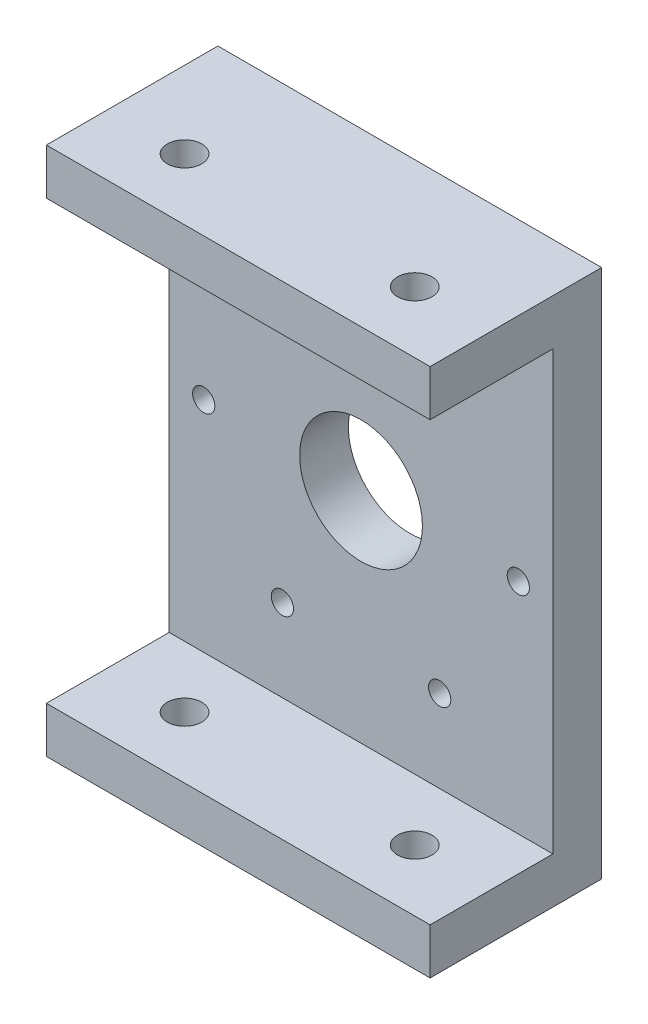
SolidWorks part; units mm, degrees
material "Aleación 6061"
ref_plane "Alzado" through (0, 0, 0) normal (0, 0, 1) x (1, 0, 0)
ref_plane "Planta" through (0, 0, 0) normal (0, 1, 0) x (1, 0, 0)
ref_plane "Vista lateral" through (0, 0, 0) normal (1, 0, 0) x (0, 0, -1)
sketch "Sk_Repisa" plane through (0, 0, 0) normal (0, 0, 1) x (1, 0, 0)
  line L1 (-25, -34.5) -> (25, -34.5)
  line L2 (-25, -34.5) -> (-25, 34.5)
  line L3 (-25, 34.5) -> (25, 34.5)
  line L4 (25, -34.5) -> (25, 34.5)
  line L5 (-25, -34.5) -> (25, 34.5) construction
  line L6 (-25, 34.5) -> (25, -34.5) construction
  point P0 (0, 0)
  dimension "D1" = 50
  dimension "D2" = 69
extrude "Repisa" add sketch "Sk_Repisa" along normal blind 6.35 from offset 519.65
sketch "Sk_Centro_motor" plane through (0, 0, 0) normal (0, 0, 1) x (1, 0, 0)
  circle A0 centre (0, 0) radius 8
  dimension "D1" = 16
extrude "Centro_motor" cut sketch "Sk_Centro_motor" along normal blind 6.35 from offset 519.65
sketch "Sk_Pasantes_M2-5_estator_J6" plane through (0, 0, 0) normal (0, 0, 1) x (1, 0, 0)
  circle A0 centre (20.5, 0) radius 1.45
  circle A1 centre (10.25, 17.7535) radius 1.45
  circle A2 centre (-10.25, 17.7535) radius 1.45
  circle A3 centre (-20.5, 0) radius 1.45
  circle A4 centre (-10.25, -17.7535) radius 1.45
  circle A5 centre (10.25, -17.7535) radius 1.45
  dimension "D1" = 2.9
  dimension "D3" = 2.9
  dimension "D6" = 2.9
  dimension "D9" = 2.9
  dimension "D11" = 2.9
  dimension "D14" = 2.9
  dimension "D2" = 20.5
  dimension "D4" = 10.25
  dimension "D5" = 17.7535
  dimension "D7" = 10.25
  dimension "D8" = 17.7535
  dimension "D10" = 20.5
  dimension "D12" = 10.25
  dimension "D13" = 17.7535
  dimension "D15" = 10.25
  dimension "D16" = 17.7535
extrude "Pasantes_M2-5_estator_J6" cut sketch "Sk_Pasantes_M2-5_estator_J6" along normal blind 6.35 from offset 519.65
sketch "Sk_Pestanas" plane through (0, 0, 0) normal (0, 0, 1) x (1, 0, 0)
  line L1 (-25, 28.5) -> (25, 28.5)
  line L2 (-25, 28.5) -> (-25, 34.5)
  line L3 (-25, 34.5) -> (25, 34.5)
  line L4 (25, 28.5) -> (25, 34.5)
  line L5 (-25, 28.5) -> (25, 34.5) construction
  line L6 (-25, 34.5) -> (25, 28.5) construction
  line L7 (-25, -34.5) -> (25, -34.5)
  line L8 (-25, -34.5) -> (-25, -28.5)
  line L9 (-25, -28.5) -> (25, -28.5)
  line L10 (25, -34.5) -> (25, -28.5)
  line L11 (-25, -34.5) -> (25, -28.5) construction
  line L12 (-25, -28.5) -> (25, -34.5) construction
  point P0 (0, 31.5)
  point P6 (0, -31.5)
  dimension "D1" = 50
  dimension "D2" = 6
  dimension "D3" = 31.5
  dimension "D4" = 50
  dimension "D5" = 6
  dimension "D6" = 31.5
extrude "Pestanas" add sketch "Sk_Pestanas" along normal blind 16 from offset 526
sketch "Sk_Pasantes_M4_pestanas" plane through (0, 0, 0) normal (0, 1, 0) x (1, 0, 0)
  circle A0 centre (-15, -534) radius 2.25
  circle A1 centre (15, -534) radius 2.25
  dimension "D1" = 4.5
  dimension "D4" = 4.5
  dimension "D2" = 15
  dimension "D3" = 534
  dimension "D5" = 15
  dimension "D6" = 534
extrude "Pasantes_M4_pestanas" cut sketch "Sk_Pasantes_M4_pestanas" along normal blind 69 from offset 34.5
